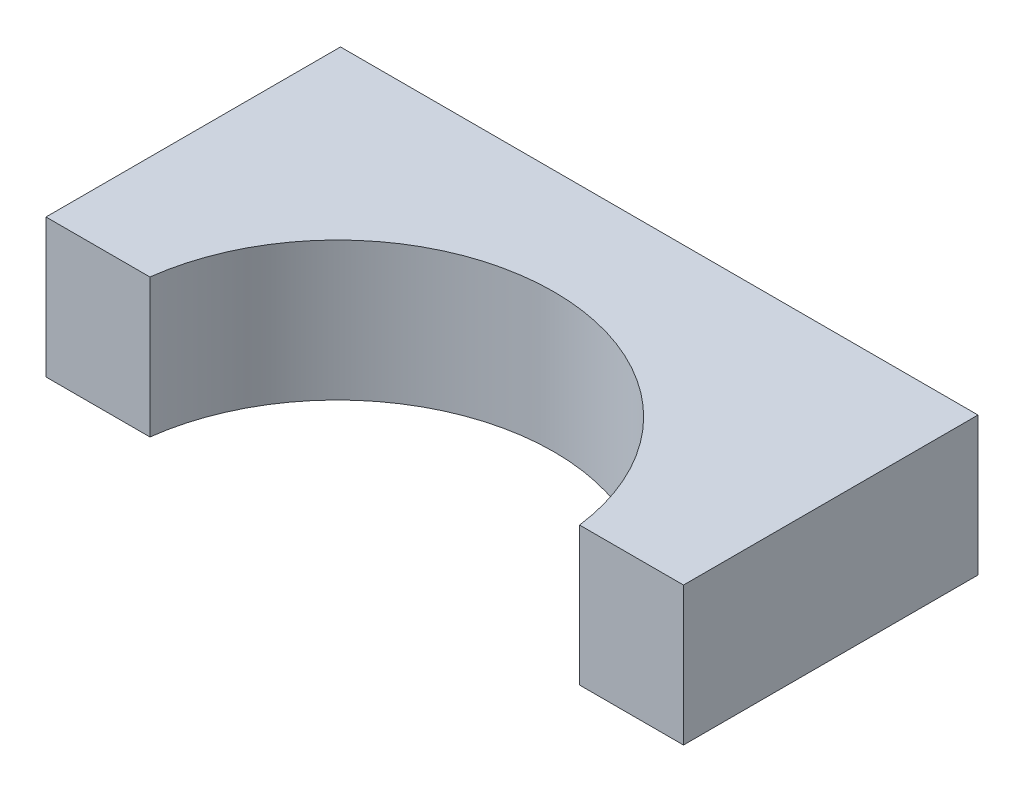
SolidWorks part; units mm, degrees
material "PLA"
ref_plane "Front" through (0, 0, 0) normal (0, 0, 1) x (1, 0, 0)
ref_plane "Top" through (0, 0, 0) normal (0, 1, 0) x (1, 0, 0)
ref_plane "Right" through (0, 0, 0) normal (1, 0, 0) x (0, 0, -1)
sketch "Sketch2" plane through (0, 0, 0) normal (0, 1, 0) x (1, 0, 0)
  line L0 (-14.986, -8.89) -> (-7.366, -8.89)
  line L1 (-14.986, 12.7) -> (31.75, 12.7)
  line L2 (-14.986, 12.7) -> (-14.986, -8.89)
  line L4 (31.75, 12.7) -> (31.75, -8.89)
  line L5 (24.13, -8.89) -> (31.75, -8.89)
  arc A3 (24.13, -8.89) -> (-7.366, -8.89) centre (8.382, -10.894) ccw
  point P0 (0, 0)
  dimension "D5" = 31.75
  dimension "D1" = 46.736
  dimension "D2" = 21.59
  dimension "D3" = 7.62
  dimension "D4" = 7.62
extrude "Boss-Extrude1" add sketch "Sketch2" against normal blind 10.16
sketch "Sketch6" plane through (0, 0, -12.7) normal (0, 0, -1) x (-1, 0, 0)
  line L0 (0, 0) -> (14.986, 0)
  line L1 (14.986, 0) -> (-31.75, 0)
  line L2 (-31.75, 0) -> (-8.382, 0)
  line L3 (-8.382, 0) -> (-8.382, -10.16)
  line L6 (-8.382, -5.08) -> (14.986, -5.08)
  line L7 (14.986, -10.16) -> (14.986, 0) construction
  line L8 (14.986, -5.08) -> (-31.75, -5.08)
  line L9 (-31.75, -10.16) -> (-31.75, 0) construction
  line L10 (-27.94, -5.08) -> (-8.382, -5.08)
  line L11 (-8.382, -5.08) -> (11.176, -5.08)
  circle A0 centre (-27.94, -5.08) radius 1.0033
  circle A1 centre (11.176, -5.08) radius 1.0033
  dimension "D2" = 2.0066
  dimension "D5" = 2.0066
  dimension "D1" = 23.368
  dimension "D3" = 19.558
  dimension "D4" = 19.558
extrude "Cut-Extrude1" cut sketch "Sketch6" against normal blind 4.064 contours L10 A0 L8 | L8 A0 L10 | L8 A1 L11 | L11 A1 L8
